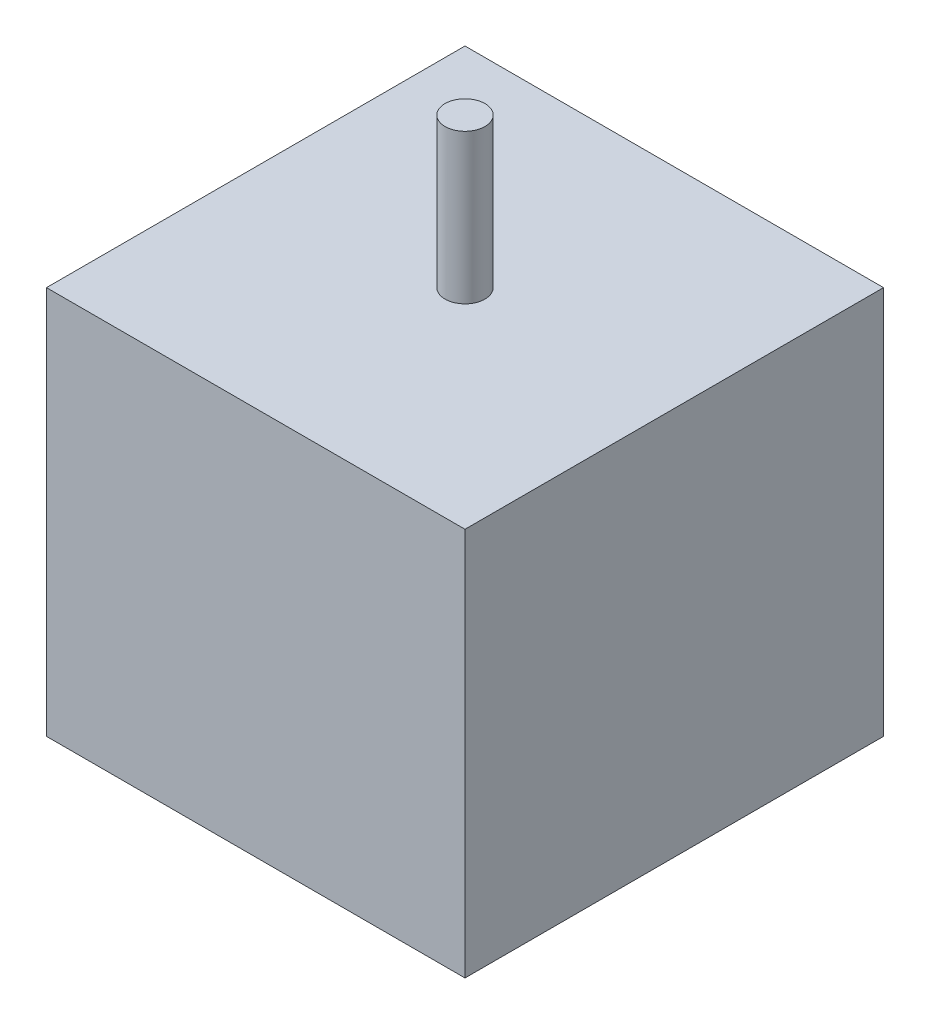
SolidWorks part; units mm, degrees
ref_plane "Plan de face" through (0, 0, 0) normal (0, 0, 1) x (1, 0, 0)
ref_plane "Plan de dessus" through (0, 0, 0) normal (0, 1, 0) x (1, 0, 0)
ref_plane "Plan de droite" through (0, 0, 0) normal (1, 0, 0) x (0, 0, -1)
sketch "Esquisse1" plane through (0, 0, 0) normal (0, 1, 0) x (1, 0, 0)
  line L1 (-21, -21) -> (21, -21)
  line L2 (-21, -21) -> (-21, 21)
  line L3 (-21, 21) -> (21, 21)
  line L4 (21, -21) -> (21, 21)
  line L5 (-21, -21) -> (21, 21) construction
  line L6 (-21, 21) -> (21, -21) construction
  point P0 (0, 0)
  dimension "D1" = 42
  dimension "D2" = 42
extrude "Boss.-Extru.1" add sketch "Esquisse1" along normal blind 39
ref_plane "Plan1" through (0, 39, 0) normal (0, 1, 0) x (1, 0, 0)
sketch "Esquisse3" plane through (0, 39, 0) normal (0, 1, 0) x (1, 0, 0)
  circle A0 centre (0, 0) radius 7.5
  dimension "D1" = 15
sketch "Esquisse4" plane through (0, 39, 0) normal (0, 1, 0) x (1, 0, 0)
  circle A0 centre (0, 0) radius 2
  dimension "D1" = 4
extrude "Boss.-Extru.2" add sketch "Esquisse4" along normal blind 15
